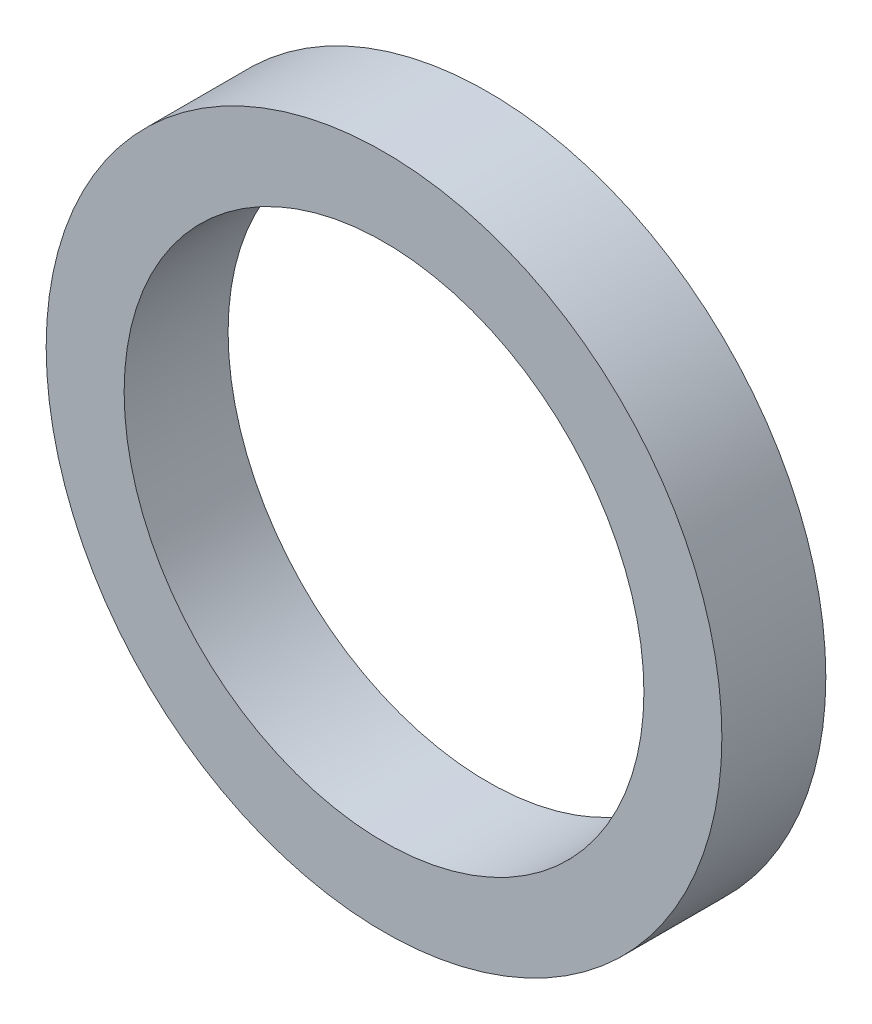
SolidWorks part; units mm, degrees
material "AISI 316 Stainless Steel Sheet (SS)"
ref_plane "Front Plane" through (0, 0, 0) normal (0, 0, 1) x (1, 0, 0)
ref_plane "Top Plane" through (0, 0, 0) normal (0, 1, 0) x (1, 0, 0)
ref_plane "Right Plane" through (0, 0, 0) normal (1, 0, 0) x (0, 0, -1)
sketch "Sketch1" plane through (0, 0, 0) normal (0, 0, 1) x (1, 0, 0)
  circle A0 centre (0, 0) radius 13
  circle A1 centre (0, 0) radius 10
  dimension "D1" = 26
  dimension "D2" = 20
extrude "Boss-Extrude1" add sketch "Sketch1" along normal blind 4
